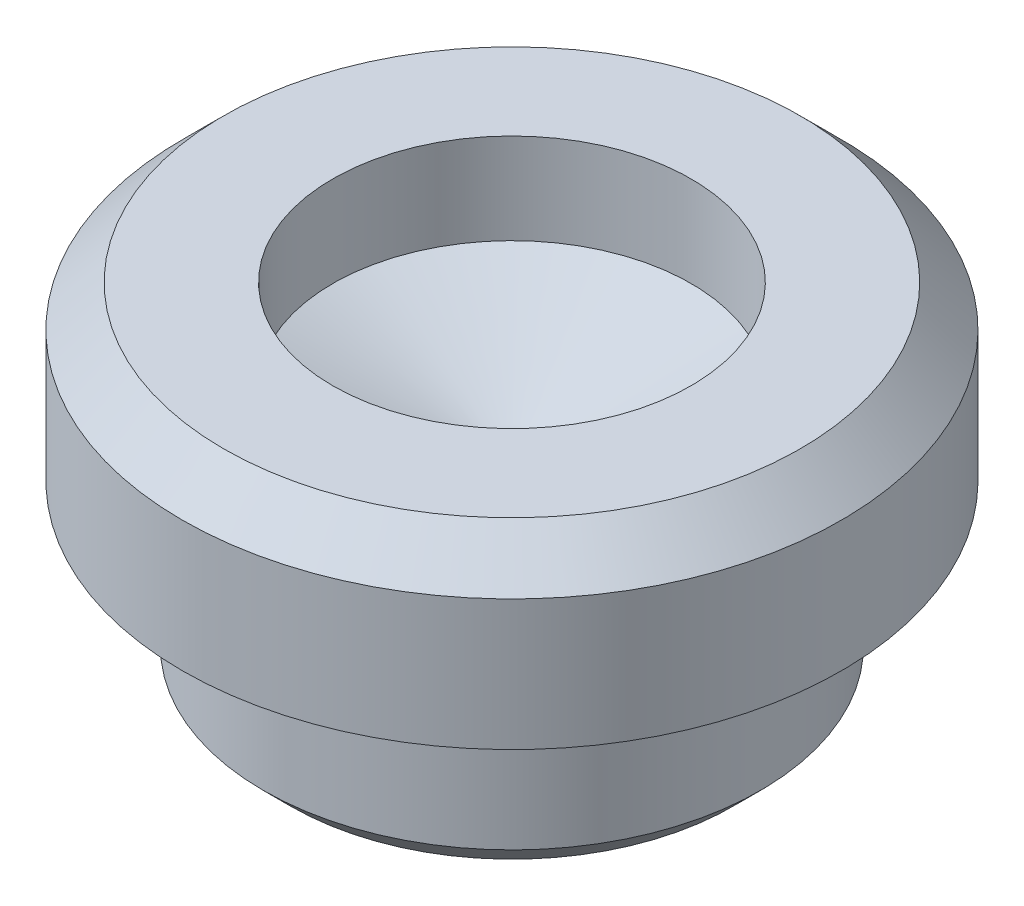
SolidWorks part; units mm, degrees
ref_plane "Front Plane" through (0, 0, 0) normal (0, 0, 1) x (1, 0, 0)
ref_plane "Top Plane" through (0, 0, 0) normal (0, 1, 0) x (1, 0, 0)
ref_plane "Right Plane" through (0, 0, 0) normal (1, 0, 0) x (0, 0, -1)
sketch "Sketch1" plane through (0, 0, 0) normal (0, 1, 0) x (1, 0, 0)
  circle A0 centre (0, 0) radius 4.5974
  dimension "D1" = 9.1948
extrude "Boss-Extrude1" add sketch "Sketch1" along normal blind 3.175
sketch "Sketch2" plane through (0, 3.175, 0) normal (0, 1, 0) x (1, 0, 0)
  circle A0 centre (0, 0) radius 6.096
  dimension "D1" = 12.192
extrude "Boss-Extrude2" add sketch "Sketch2" along normal blind 3.175
chamfer "Chamfer1" distance 0.762 angle 45 1 edges at (0, 6.35, 6.096)
chamfer "Chamfer2" distance 0.508 angle 45 1 edges at (0, 0, 4.5974)
sketch "Sketch3" plane through (0, 6.35, 0) normal (0, 1, 0) x (1, 0, 0)
  circle A0 centre (0, 0) radius 3.3147
  dimension "D1" = 6.6294
extrude "Cut-Extrude1" cut sketch "Sketch3" against normal blind 1.6764
sketch "Sketch5" plane through (0, 4.6736, 0) normal (0, 1, 0) x (1, 0, 0)
  circle A0 centre (0, 0) radius 3.3147 construction
  circle A1 centre (0, 0) radius 3.3147
extrude "Cut-Extrude2" cut sketch "Sketch5" against normal through all draft 68
